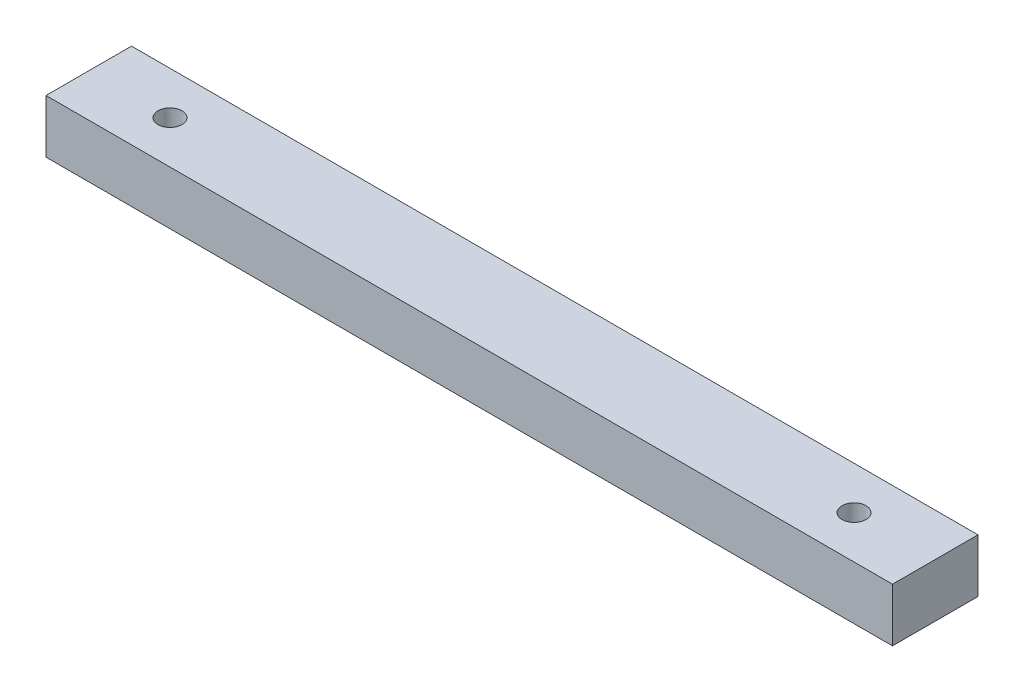
SolidWorks part; units mm, degrees
material "Galvanized Steel"
ref_plane "Front Plane" through (0, 0, 0) normal (0, 0, 1) x (1, 0, 0)
ref_plane "Top Plane" through (0, 0, 0) normal (0, 1, 0) x (1, 0, 0)
ref_plane "Right Plane" through (0, 0, 0) normal (1, 0, 0) x (0, 0, -1)
sketch "Sketch3" plane through (0, 0, 0) normal (1, 0, 0) x (0, 0, -1)
  line L0 (-12.7, -7.9375) -> (12.7, 7.9375) construction
  line L1 (-12.7, 7.9375) -> (12.7, 7.9375)
  line L2 (-12.7, 7.9375) -> (-12.7, -7.9375)
  line L3 (-12.7, -7.9375) -> (12.7, -7.9375)
  line L4 (12.7, 7.9375) -> (12.7, -7.9375)
  dimension "D1" = 25.4
  dimension "D2" = 15.875
extrude "Extrude2" add sketch "Sketch3" along normal mid plane 251.46
sketch "Sketch5" plane through (0, 7.9375, 0) normal (0, 1, 0) x (-1, 0, 0)
  line L0 (-101.6, 0) -> (101.6, 0) construction
  dimension "D1" = 203.2
hole_wizard "1/4 Clearance Hole1" positions "3DSketch2" profile "Sketch6" hole size "1/4" standard "Ansi Inch" end condition through all
sketch3d "3DSketch2"
  point P0 (101.6, 7.9375, 0)
  point P3 (-101.6, 7.9375, 0)
sketch "Sketch6" plane through (101.6, 7.9375, 0) normal (1, 0, 0) x (0, 0, 1)
  line L0 (0, 0) -> (0, 15.875)
  line L1 (0, 15.875) -> (3.5712, 15.875)
  line L2 (3.5712, 15.875) -> (3.5712, 0)
  line L5 (3.5712, 0) -> (0, 0)
  line L11 (0, -6.35) -> (0, 107.95) construction
  dimension "Thru Hole Dia." = 7.1425
  dimension "Thru Hole Depth" = 15.875
